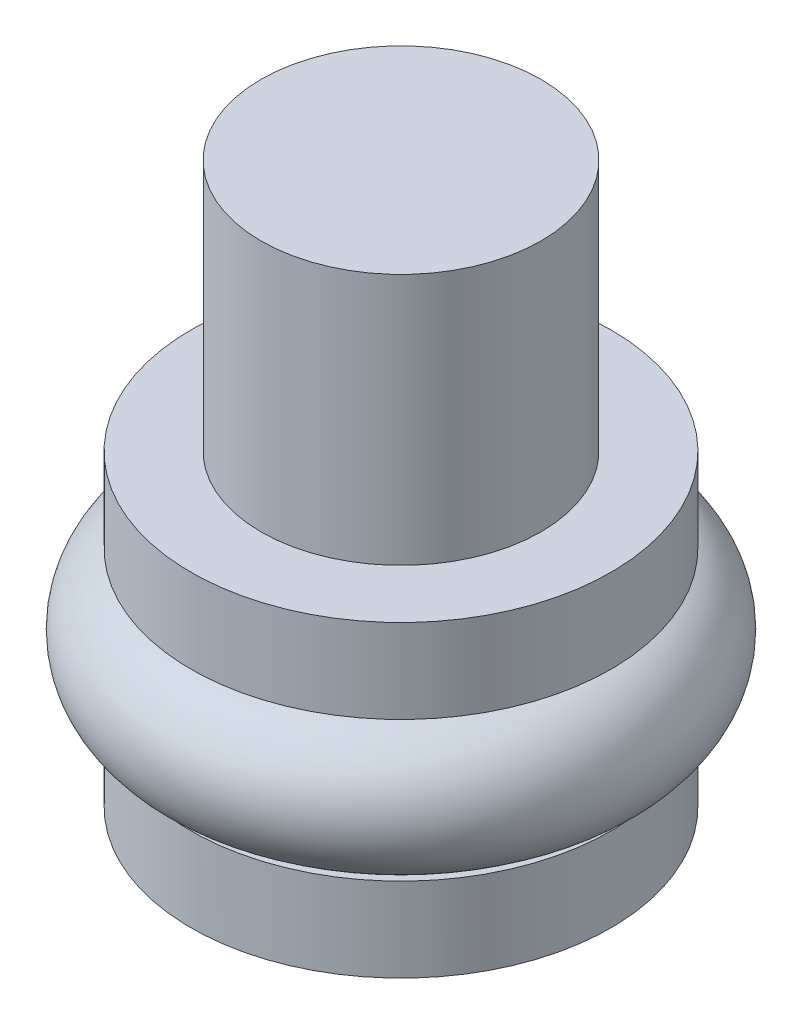
SolidWorks part; units mm, degrees
ref_plane "Front Plane" through (0, 0, 0) normal (0, 0, 1) x (1, 0, 0)
ref_plane "Top Plane" through (0, 0, 0) normal (0, 1, 0) x (1, 0, 0)
ref_plane "Right Plane" through (0, 0, 0) normal (1, 0, 0) x (0, 0, -1)
sketch "Sketch1" plane through (0, 0, 0) normal (0, 1, 0) x (1, 0, 0)
  circle A0 centre (0, 0) radius 5
  dimension "D1" = 10
extrude "Boss-Extrude1" add sketch "Sketch1" along normal blind 9
sketch "Sketch2" plane through (0, 0, 0) normal (0, -1, 0) x (-1, 0, 0)
  circle A0 centre (0, 0) radius 7.5
  dimension "D1" = 15
extrude "Boss-Extrude2" add sketch "Sketch2" along normal blind 3
ref_plane "Plane1" through (0, -5.5, 0) normal (0, -1, 0) x (-1, 0, 0)
sketch "Sketch3" plane through (0, -5.5, 0) normal (0, -1, 0) x (-1, 0, 0)
  line L0 (0, 9.1629) -> (0, -9.1629) construction
  circle A0 centre (0, 0) radius 6.5
  dimension "D1" = 13
sketch "Sketch5" plane through (0, 0, 0) normal (1, 0, 0) x (0, 0, -1)
  line L0 (-6.5, -5.5) -> (6.5, -5.5) construction
  line L1 (-8.25, -5.5) -> (8.25, -5.5) construction
  circle A0 centre (-6.5, -5.5) radius 2.4611
sweep "Sweep1" add profiles "Sketch5" path "Sketch3"
ref_plane "Plane2" through (0, -8, 0) normal (0, -1, 0) x (-1, 0, 0)
sketch "Sketch12" plane through (0, -8, 0) normal (0, -1, 0) x (-1, 0, 0)
  circle A0 centre (0, 0) radius 7.5
  dimension "D1" = 15
extrude "Boss-Extrude3" add sketch "Sketch12" along normal blind 3 separate body
sketch "Sketch13" plane through (0, 0, 0) normal (0, 0, 1) x (1, 0, 0)
  line L0 (0, -11) -> (0, -13)
  line L1 (-7.5, -11) -> (7.5, -11) construction
  line L2 (0, -13) -> (7.5, -11)
  line L3 (0, -11) -> (7.5, -11)
  dimension "D1" = 2
revolve "Revolve1" add sketch "Sketch13" angle 360 about L0
